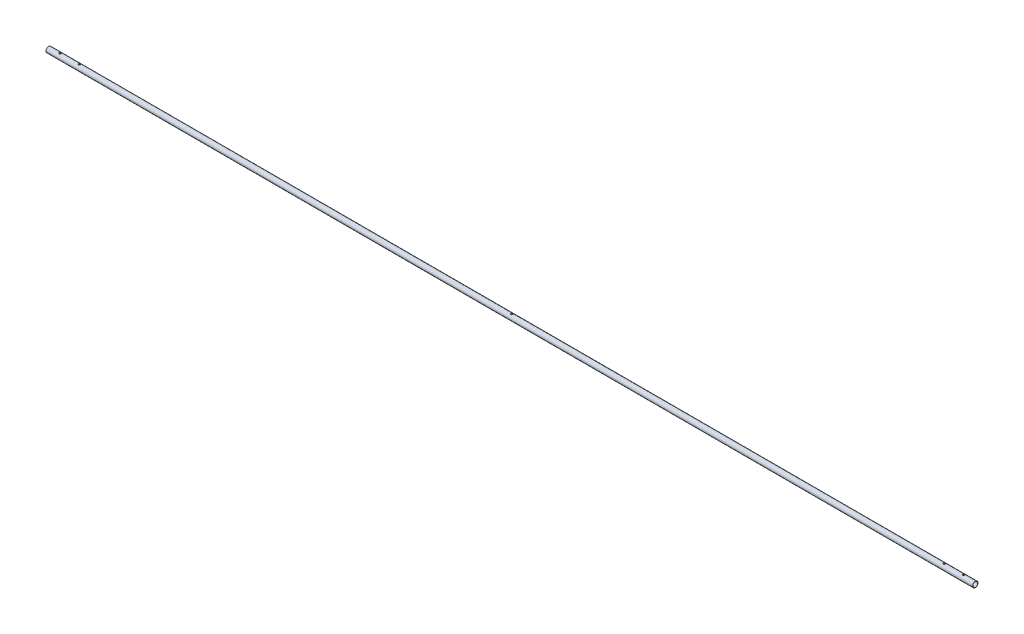
SolidWorks part; units mm, degrees
material "Galvanized Steel"
ref_plane "Front Plane" through (0, 0, 0) normal (0, 0, 1) x (1, 0, 0)
ref_plane "Top Plane" through (0, 0, 0) normal (0, 1, 0) x (1, 0, 0)
ref_plane "Right Plane" through (0, 0, 0) normal (1, 0, 0) x (0, 0, -1)
sketch "Sketch1" plane through (0, 0, 0) normal (1, 0, 0) x (0, 0, -1)
  circle A0 centre (0, 0) radius 7.8994
  circle A1 centre (0, 0) radius 8.9662
  dimension "D1" = 15.7988
  dimension "D2" = 17.9324
extrude "Boss-Extrude1" add sketch "Sketch1" along normal blind 3048
sketch "Sketch2" plane through (0, 0, 0) normal (0, 1, 0) x (1, 0, 0)
  line L0 (0, 8.9662) -> (0, -8.9662) construction
  line L1 (3048, -8.9662) -> (3048, 8.9662) construction
  circle A0 centre (38.1, 0) radius 3.175
  circle A1 centre (3009.9, 0) radius 3.175
  circle A2 centre (101.6, 0) radius 3.175
  circle A3 centre (2946.4, 0) radius 3.175
  dimension "D1" = 6.35
  dimension "D3" = 6.35
  dimension "D5" = 6.35
  dimension "D7" = 6.35
  dimension "D2" = 38.1
  dimension "D4" = 38.1
  dimension "D6" = 101.6
  dimension "D8" = 101.6
sketch "Sketch3" plane through (0, 0, 0) normal (0, 1, 0) x (1, 0, 0)
  line L0 (0, 8.9662) -> (0, -8.9662) construction
  circle A0 centre (1524, 0) radius 3.175
  dimension "D1" = 6.35
  dimension "D2" = 1524
extrude "Cut-Extrude2" cut sketch "Sketch3" against normal through all and the other way through all
extrude "Cut-Extrude5" cut sketch "Sketch2" against normal through all and the other way through all
